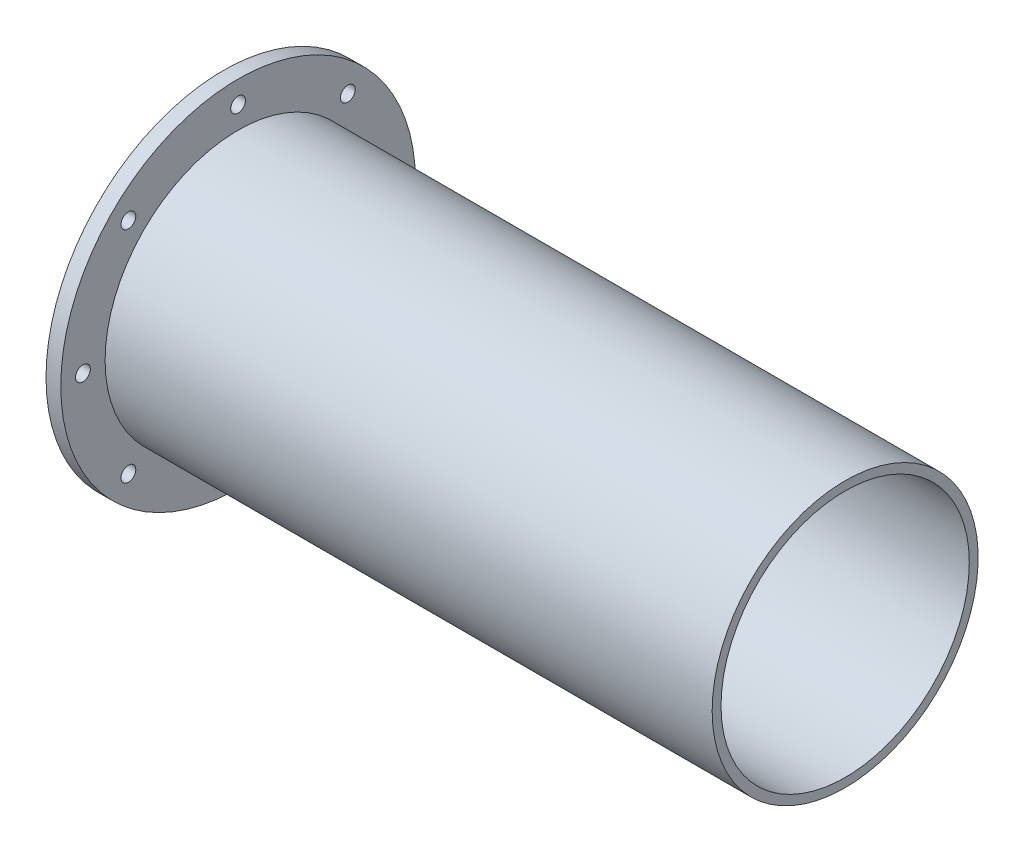
SolidWorks part; units mm, degrees
ref_plane "Front Plane" through (0, 0, 0) normal (0, 0, 1) x (1, 0, 0)
ref_plane "Top Plane" through (0, 0, 0) normal (0, 1, 0) x (1, 0, 0)
ref_plane "Right Plane" through (0, 0, 0) normal (1, 0, 0) x (0, 0, -1)
sketch "Sketch1" plane through (0, 0, 0) normal (0, 0, 1) x (1, 0, 0)
  line L0 (0, 53.34) -> (267.208, 53.34)
  line L1 (267.208, 53.34) -> (267.208, 57.15)
  line L2 (267.208, 57.15) -> (6.35, 57.15)
  line L3 (6.35, 57.15) -> (6.35, 76.2)
  line L4 (6.35, 76.2) -> (0, 76.2)
  line L5 (0, 76.2) -> (0, 53.34)
  line L6 (0, 0) -> (0, 53.34) construction
  line L7 (0, 0) -> (208.8552, 0) construction
  dimension "D1" = 3.81
  dimension "D2" = 6.35
  dimension "D3" = 76.2
  dimension "D4" = 57.15
  dimension "D5" = 267.208
revolve "Revolve1" add sketch "Sketch1" angle 360 about L7
sketch "Sketch2" plane through (6.35, 0, 0) normal (1, 0, 0) x (0, 0, -1)
  line L0 (0, 0) -> (-92.9633, 0) construction
  circle A0 centre (-66.675, 0) radius 3.175
  dimension "D1" = 6.35
  dimension "D2" = 66.675
extrude "Cut-Extrude1" cut sketch "Sketch2" against normal through all
pattern_circular "CirPattern1" count 8 over 360 about axis through (0, 0, 0) along (1, 0, 0) of "Cut-Extrude1"
